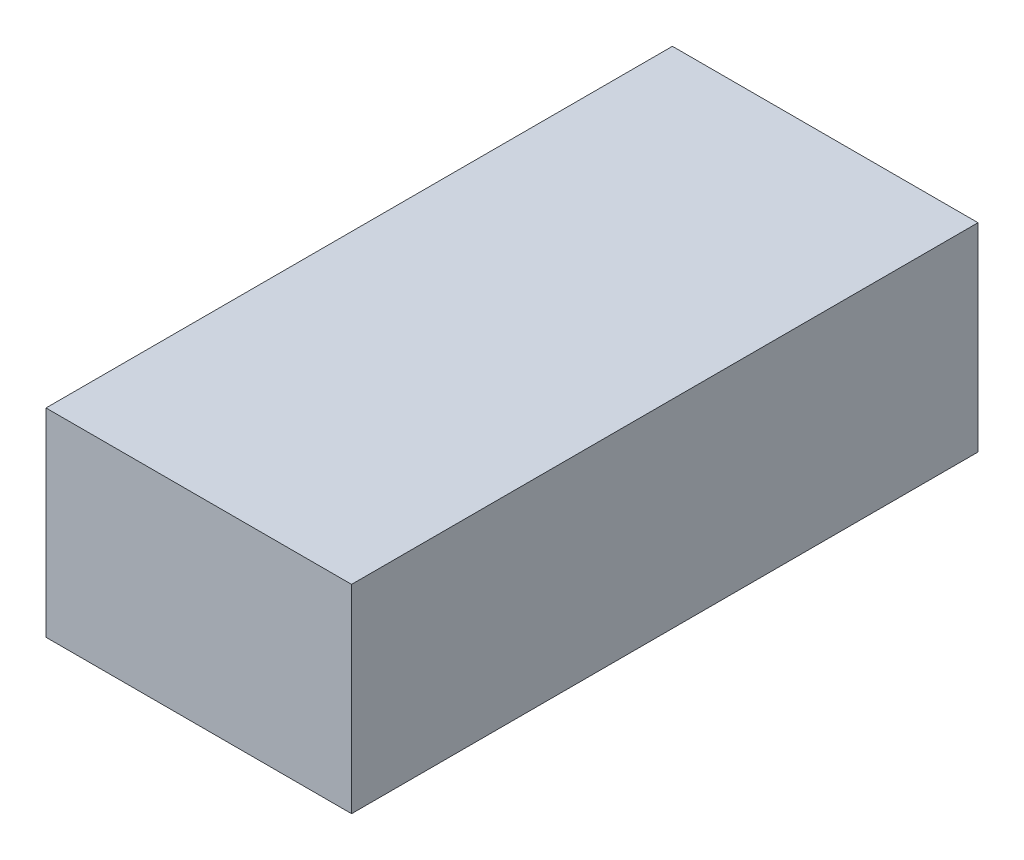
SolidWorks part; units mm, degrees
ref_plane "Front Plane" through (0, 0, 0) normal (0, 0, 1) x (1, 0, 0)
ref_plane "Top Plane" through (0, 0, 0) normal (0, 1, 0) x (1, 0, 0)
ref_plane "Right Plane" through (0, 0, 0) normal (1, 0, 0) x (0, 0, -1)
sketch "Sketch1" plane through (0, 0, 0) normal (0, 1, 0) x (1, 0, 0)
  line L2 (-10, 20.5) -> (10, 20.5)
  line L3 (-10, 20.5) -> (-10, -20.5)
  line L4 (-10, -20.5) -> (10, -20.5)
  line L5 (10, 20.5) -> (10, -20.5)
  line L6 (-10, 20.5) -> (10, -20.5) construction
  line L7 (-10, -20.5) -> (10, 20.5) construction
  point P1 (0, 0)
  dimension "D1" = 20
  dimension "D2" = 41
extrude "Boss-Extrude1" add sketch "Sketch1" along normal blind 13
